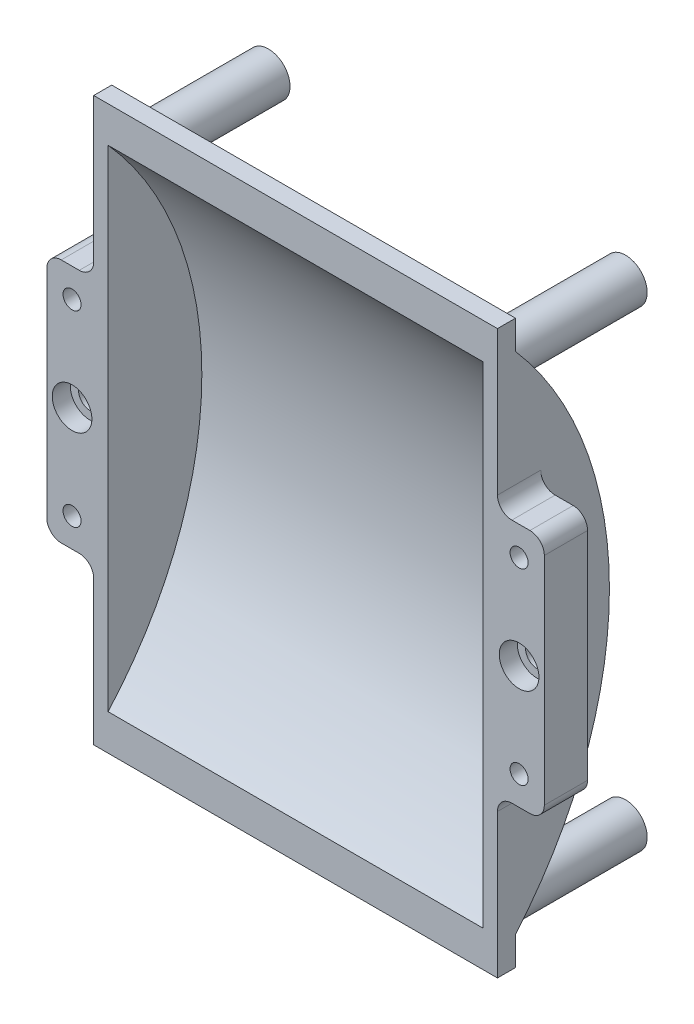
SolidWorks part; units mm, degrees
material "ABS"
ref_plane "前视基准面" through (0, 0, 0) normal (0, 0, 1) x (1, 0, 0)
ref_plane "上视基准面" through (0, 0, 0) normal (0, 1, 0) x (1, 0, 0)
ref_plane "右视基准面" through (0, 0, 0) normal (1, 0, 0) x (0, 0, -1)
sketch "草图1" plane through (0, 0, 0) normal (0, 0, 1) x (1, 0, 0)
  line L0 (0, 0) -> (31, 0) construction
  line L1 (28, -36) -> (-28, -36)
  line L2 (28, -36) -> (28, 36)
  line L3 (28, 36) -> (-28, 36)
  line L4 (-28, -36) -> (-28, 36)
  line L5 (28, -36) -> (-28, 36) construction
  line L6 (28, 36) -> (-28, -36) construction
  line L8 (-24.765, -32.705) -> (24.765, -32.705)
  line L9 (-24.765, -32.705) -> (-24.765, 32.705)
  line L10 (-24.765, 32.705) -> (24.765, 32.705)
  line L11 (24.765, -32.705) -> (24.765, 32.705)
  line L12 (-24.765, -32.705) -> (24.765, 32.705) construction
  line L13 (-24.765, 32.705) -> (24.765, -32.705) construction
  circle A0 centre (31, 0) radius 1.1731
  circle A1 centre (-24.765, 32.705) radius 1.6
  point P0 (0, 0)
  dimension "D6" = 3.2
  dimension "D1" = 56
  dimension "D2" = 31
  dimension "D3" = 72
  dimension "D4" = 49.53
  dimension "D5" = 65.41
sketch "草图2" plane through (0, 0, 0) normal (1, 0, 0) x (0, 0, -1)
  line L0 (0, -36) -> (0, 36) construction
  line L1 (0, 36) -> (0, -36) construction
  line L2 (0, 34.0147) -> (0, 39)
  line L3 (-38, 0) -> (13, 0) construction
  line L4 (0, 39) -> (2.5, 39)
  line L5 (2.5, 39) -> (2.5, 35)
  line L6 (2.5, -39) -> (2.5, -35)
  line L7 (0, -34.0147) -> (0, -39)
  line L8 (0, -39) -> (2.5, -39)
  arc A0 (0, 34.0147) -> (0, -34.0147) centre (-38, 0) cw
  circle A1 centre (-38, 0) radius 46 construction
  arc A2 (2.5, 35) -> (2.5, -35) centre (-38, 0) cw
  dimension "D2" = 92
  dimension "D4" = 5
  dimension "D1" = 38
  dimension "D3" = 3
  dimension "D5" = 4
  dimension "D6" = 2.5
extrude "凸台-拉伸1" add sketch "草图2" along normal mid plane 52
sketch "草图3" plane through (26, 0, 0) normal (1, 0, 0) x (0, 0, -1)
  line L0 (0, 39) -> (0, -39)
  line L1 (0, -39) -> (2.5, -39)
  line L2 (2.5, -39) -> (2.5, -35)
  line L3 (0, 39) -> (2.5, 39)
  line L4 (2.5, 39) -> (2.5, 35)
  arc A0 (2.5, 35) -> (2.5, -35) centre (-38, 0) cw
extrude "凸台-拉伸2" add sketch "草图3" along normal blind 2
sketch "草图4" plane through (-26, 0, 0) normal (-1, 0, 0) x (0, 0, 1)
  line L0 (-2.5, 35) -> (-2.5, 39)
  line L1 (-2.5, 39) -> (0, 39)
  line L2 (0, 39) -> (0, -39)
  line L3 (0, -39) -> (-2.5, -39)
  line L4 (-2.5, -39) -> (-2.5, -35)
  arc A0 (-2.5, -35) -> (-2.5, 35) centre (38, 0) cw
extrude "凸台-拉伸3" add sketch "草图4" along normal blind 2
sketch "草图7" plane through (0, 0, 0) normal (0, 0, 1) x (1, 0, 0)
  line L0 (28, 17) -> (34.5, 17)
  line L1 (28, -36) -> (28, 36) construction
  line L2 (34.5, 17) -> (34.5, -17)
  line L3 (34.5, -17) -> (28, -17)
  line L4 (28, -17) -> (28, 17)
  line L5 (0, 0) -> (31, 0) construction
  line L6 (0, 0) -> (0, 39) construction
  line L7 (28, 39) -> (-28, 39) construction
  line L8 (0, 0) -> (31, 0) construction
  line L9 (-34.5, -17) -> (-28, -17)
  line L10 (-34.5, 17) -> (-34.5, -17)
  line L11 (-28, 17) -> (-34.5, 17)
  line L12 (-28, -17) -> (-28, 17)
  circle A0 centre (31, 0) radius 1.6
  circle A1 centre (31, 13) radius 1.25
  circle A2 centre (31, -13) radius 1.25
  circle A3 centre (-31, -13) radius 1.25
  circle A4 centre (-31, 0) radius 1.6
  circle A5 centre (-31, 13) radius 1.25
  dimension "D4" = 3.2
  dimension "D5" = 2.5
  dimension "D6" = 13
  dimension "D1" = 6.5
  dimension "D2" = 34
  dimension "D3" = 17
extrude "凸台-拉伸4" add sketch "草图7" against normal blind 6
fillet "圆角1" radius 2 8 edges at (-34.5, -17, -3) (-28, -17, -3) (-34.5, 17, -3) (-28, 17, -3) (28, -17, -3) (34.5, -17, -3) (34.5, 17, -3) (28, 17, -3)
ref_plane "基准面4" through (0, 0, -21) normal (0, 0, 1) x (1, 0, 0)
sketch "草图9" plane through (0, 0, -21) normal (0, 0, 1) x (1, 0, 0)
  line L0 (0, 0) -> (0, 39) construction
  line L2 (28, 39) -> (-28, 39) construction
  line L3 (0, 0) -> (31, 0) construction
  line L4 (0, 0) -> (31, 0) construction
  circle A0 centre (-24.765, 32.705) radius 1.35
  circle A1 centre (-24.765, 32.705) radius 3
  circle A2 centre (24.765, 32.705) radius 1.35
  circle A3 centre (24.765, 32.705) radius 3
  circle A4 centre (24.765, -32.705) radius 1.35
  circle A5 centre (24.765, -32.705) radius 3
  circle A6 centre (-24.765, -32.705) radius 1.35
  circle A7 centre (-24.765, -32.705) radius 3
  dimension "D1" = 6
  dimension "D2" = 2.7
extrude "凸台-拉伸5" add sketch "草图9" along normal up to surface (18.5 mm away) up to face at (0, 37, -2.5)
sketch "草图10" plane through (0, 0, 0) normal (0, 0, 1) x (1, 0, 0)
  circle A0 centre (-31, 0) radius 2.75
  circle A1 centre (31, 0) radius 2.75
  dimension "D1" = 5.5
  dimension "D2" = 5.5
extrude "切除-拉伸1" cut sketch "草图10" against normal blind 2.5
sketch "草图12" plane through (0, 0, 0) normal (1, 0, 0) x (0, 0, -1)
  line L0 (0, 34.0147) -> (0, -34.0147)
  arc A0 (0, 34.0147) -> (0, -34.0147) centre (-38, 0) cw
extrude "切除-拉伸4" cut sketch "草图12" against normal mid plane 52
